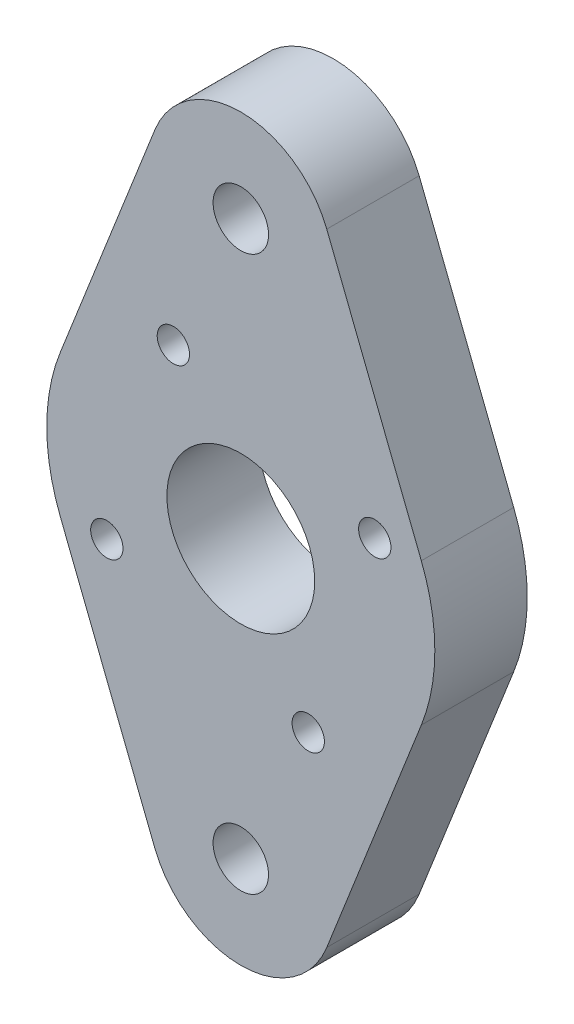
SolidWorks part; units mm, degrees
ref_plane "Plan de face" through (0, 0, 0) normal (0, 0, 1) x (1, 0, 0)
ref_plane "Plan de dessus" through (0, 0, 0) normal (0, 1, 0) x (1, 0, 0)
ref_plane "Plan de droite" through (0, 0, 0) normal (1, 0, 0) x (0, 0, -1)
sketch "Esquisse1" plane through (0, 0, 0) normal (0, 0, 1) x (1, 0, 0)
  line L0 (0, 0) -> (7.25, 0) construction
  line L1 (7.25, 3.65) -> (7.25, 0) construction
  line L2 (0, 0) -> (7.25, 0) construction
  line L3 (0, 0) -> (0, 15) construction
  line L4 (-9.7687, 3.85) -> (-4.6518, 16.8333)
  line L5 (4.6518, 16.8333) -> (9.7687, 3.85)
  line L6 (0, 0) -> (-11, 0) construction
  line L7 (4.6518, -16.8333) -> (9.7687, -3.85)
  line L8 (-9.7687, -3.85) -> (-4.6518, -16.8333)
  circle A0 centre (0, 0) radius 10.5 construction
  circle A1 centre (0, 0) radius 4
  circle A2 centre (7.25, 0) radius 0.875 construction
  circle A3 centre (7.25, 3.65) radius 0.875
  circle A4 centre (7.25, -3.65) radius 0.875 construction
  circle A5 centre (3.65, -7.25) radius 0.875
  circle A6 centre (0, -7.25) radius 0.875 construction
  circle A7 centre (-3.65, -7.25) radius 0.875 construction
  circle A8 centre (-7.25, -3.65) radius 0.875
  circle A9 centre (-7.25, 0) radius 0.875 construction
  circle A10 centre (-7.25, 3.65) radius 0.875 construction
  circle A11 centre (-3.65, 7.25) radius 0.875
  circle A12 centre (0, 7.25) radius 0.875 construction
  circle A13 centre (3.65, 7.25) radius 0.875 construction
  circle A14 centre (0, 15) radius 1.5
  arc A15 (-4.6518, 16.8333) -> (4.6518, 16.8333) centre (0, 15) cw
  arc A16 (-9.7687, -3.85) -> (-9.7687, 3.85) centre (0, 0) cw
  arc A17 (9.7687, -3.85) -> (9.7687, 3.85) centre (0, 0) ccw
  circle A18 centre (0, -15) radius 1.5
  arc A19 (-4.6518, -16.8333) -> (4.6518, -16.8333) centre (0, -15) ccw
  dimension "D1" = 21
  dimension "D2" = 8
  dimension "D5" = 1.75
  dimension "D8" = 5
  dimension "D9" = 10.5
  dimension "D10" = 3
  dimension "D3" = 7.25
  dimension "D4" = 3.65
  dimension "D7" = 15
  dimension "D6" = 4
extrude "Boss.-Extru.1" add sketch "Esquisse1" along normal blind 5
